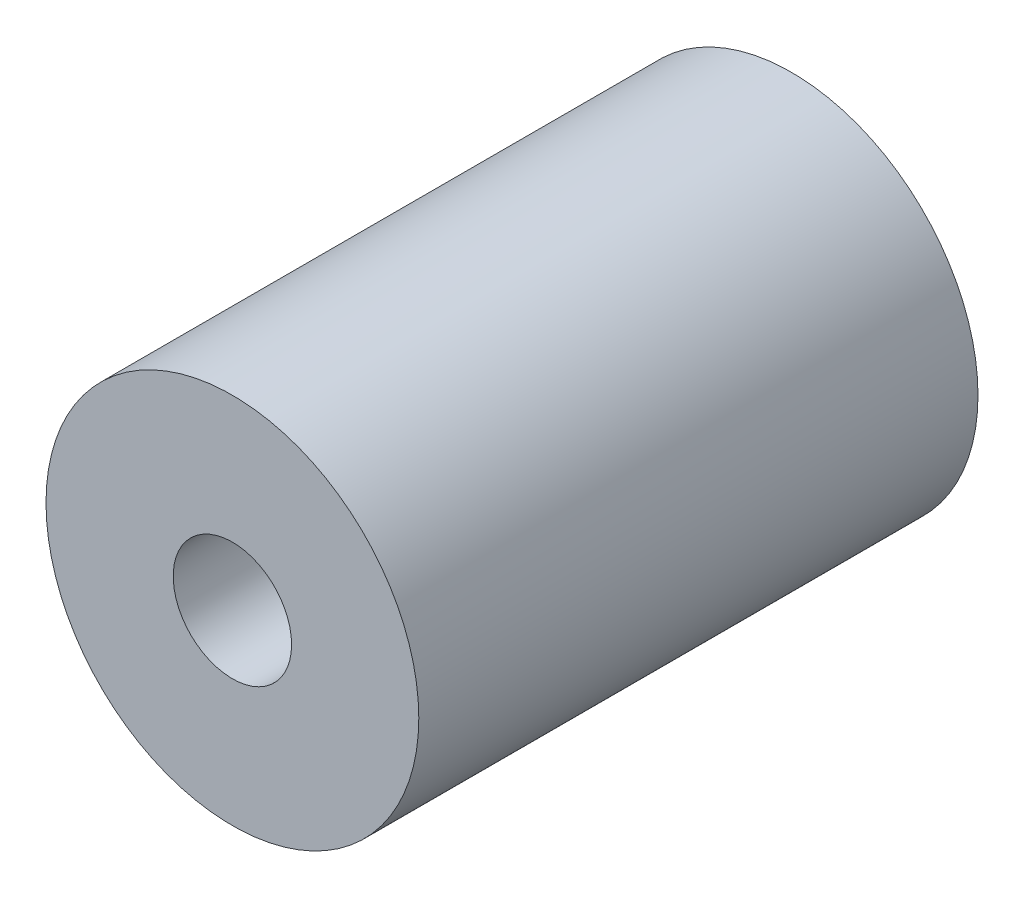
SolidWorks part; units mm, degrees
material "201 Acero inoxidable recocido (SS)"
ref_plane "Alzado" through (0, 0, 0) normal (0, 0, 1) x (1, 0, 0)
ref_plane "Planta" through (0, 0, 0) normal (0, 1, 0) x (1, 0, 0)
ref_plane "Vista lateral" through (0, 0, 0) normal (1, 0, 0) x (0, 0, -1)
sketch "Croquis1" plane through (0, 0, 0) normal (0, 0, 1) x (1, 0, 0)
  circle A0 centre (0, 0) radius 3.175
  circle A1 centre (0, 0) radius 10
  dimension "D1" = 6.35
  dimension "D2" = 20
extrude "Saliente-Extruir1" add sketch "Croquis1" along normal blind 30
